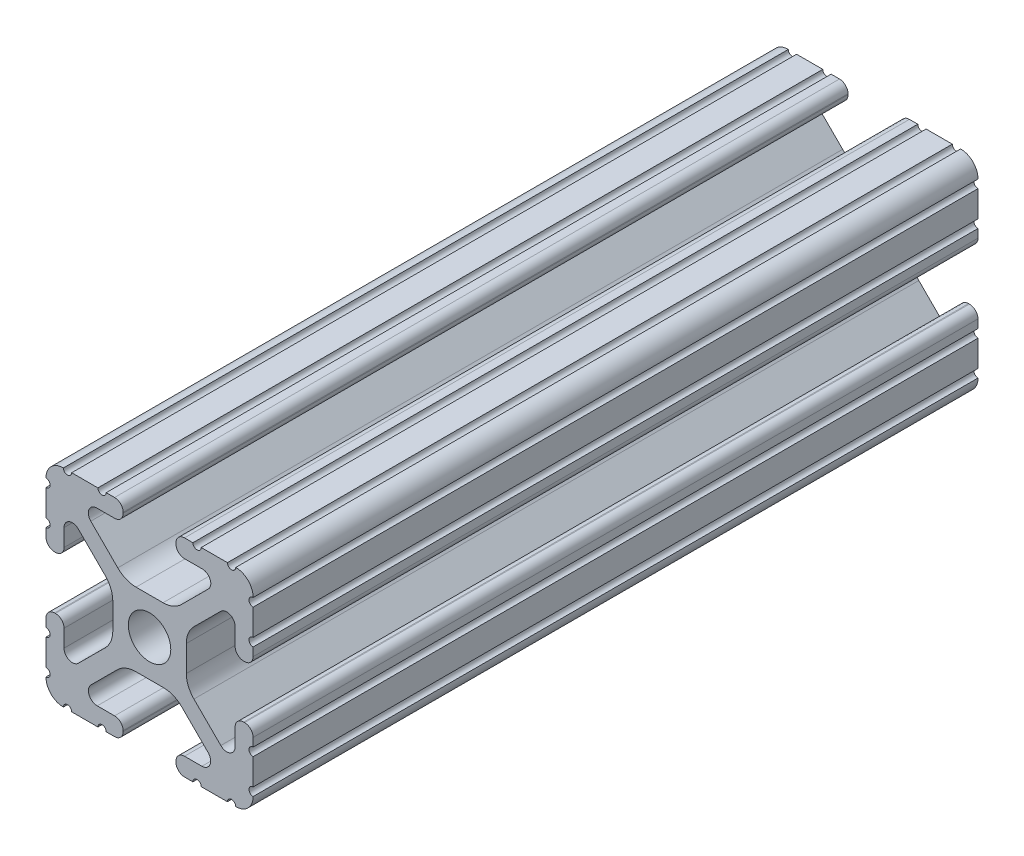
SolidWorks part; units mm, degrees
ref_plane "Front Plane" through (0, 0, 0) normal (0, 0, 1) x (1, 0, 0)
ref_plane "Top Plane" through (0, 0, 0) normal (0, 1, 0) x (1, 0, 0)
ref_plane "Right Plane" through (0, 0, 0) normal (1, 0, 0) x (0, 0, -1)
sketch "Sketch1" plane through (0, 0, 0) normal (0, 0, 1) x (1, 0, 0)
  line L88 (-7.1797, -8.6452) -> (-3.9523, -5.4237)
  line L89 (-1.7093, -4.4958) -> (1.7093, -4.4958)
  line L90 (3.9523, -5.4237) -> (7.1797, -8.6452)
  line L91 (6.4164, -10.4902) -> (4.2875, -10.4902)
  line L92 (3.2385, -11.5392) -> (3.2385, -11.651)
  line L93 (4.2875, -12.7) -> (5.3171, -12.7)
  line L94 (6.3331, -12.7) -> (9.5504, -12.7)
  line L95 (12.7, -9.5504) -> (12.7, -6.3331)
  line L96 (12.7, -5.3171) -> (12.7, -4.2875)
  line L97 (11.651, -3.2385) -> (11.5392, -3.2385)
  line L98 (10.4902, -4.2875) -> (10.4902, -6.4021)
  line L99 (8.7371, -7.1294) -> (5.441, -3.8408)
  line L100 (4.5085, -1.5932) -> (4.5085, 1.5932)
  line L101 (5.441, 3.8408) -> (8.7371, 7.1294)
  line L102 (10.4902, 6.4021) -> (10.4902, 4.2875)
  line L103 (11.5392, 3.2385) -> (11.651, 3.2385)
  line L104 (12.7, 4.2875) -> (12.7, 5.3171)
  line L105 (12.7, 6.3331) -> (12.7, 9.5504)
  line L106 (9.5504, 12.7) -> (6.3331, 12.7)
  line L107 (5.3171, 12.7) -> (4.2875, 12.7)
  line L108 (3.2385, 11.651) -> (3.2385, 11.5392)
  line L109 (4.2875, 10.4902) -> (6.4768, 10.4902)
  line L110 (7.207, 8.7244) -> (3.8983, 5.4232)
  line L111 (1.6558, 4.4958) -> (-1.6558, 4.4958)
  line L112 (-3.8983, 5.4232) -> (-7.207, 8.7244)
  line L113 (-6.4768, 10.4902) -> (-4.2875, 10.4902)
  line L114 (-3.2385, 11.5392) -> (-3.2385, 11.651)
  line L115 (-4.2875, 12.7) -> (-5.3171, 12.7)
  line L116 (-6.3331, 12.7) -> (-9.5504, 12.7)
  line L117 (-12.7, 9.5504) -> (-12.7, 6.3331)
  line L118 (-12.7, 5.3171) -> (-12.7, 4.2875)
  line L119 (-11.651, 3.2385) -> (-11.5392, 3.2385)
  line L120 (-10.4902, 4.2875) -> (-10.4902, 6.4021)
  line L121 (-8.7371, 7.1294) -> (-5.441, 3.8408)
  line L122 (-4.5085, 1.5932) -> (-4.5085, -1.5932)
  line L123 (-5.441, -3.8408) -> (-8.7371, -7.1294)
  line L124 (-10.4902, -6.4021) -> (-10.4902, -4.2875)
  line L125 (-11.5392, -3.2385) -> (-11.651, -3.2385)
  line L126 (-12.7, -4.2875) -> (-12.7, -5.3171)
  line L127 (-12.7, -6.3331) -> (-12.7, -9.5504)
  line L128 (-9.5504, -12.7) -> (-6.3331, -12.7)
  line L129 (-5.3171, -12.7) -> (-4.2875, -12.7)
  line L130 (-3.2385, -11.651) -> (-3.2385, -11.5392)
  line L131 (-4.2875, -10.4902) -> (-6.4164, -10.4902)
  circle A1 centre (0, 0) radius 2.6035
  arc A104 (-7.1797, -8.6452) -> (-6.4164, -10.4902) centre (-6.4164, -9.4098) ccw
  arc A105 (-1.7093, -4.4958) -> (-3.9523, -5.4237) centre (-1.7093, -7.6708) ccw
  arc A106 (3.9523, -5.4237) -> (1.7093, -4.4958) centre (1.7093, -7.6708) ccw
  arc A107 (6.4164, -10.4902) -> (7.1797, -8.6452) centre (6.4164, -9.4098) ccw
  arc A108 (4.2875, -10.4902) -> (3.2385, -11.5392) centre (4.2875, -11.5392) ccw
  arc A109 (3.2385, -11.651) -> (4.2875, -12.7) centre (4.2875, -11.651) ccw
  arc A110 (6.3331, -12.7) -> (5.3171, -12.7) centre (5.8251, -12.7) ccw
  arc A111 (10.5664, -12.6998) -> (9.5504, -12.7) centre (10.0584, -12.7) ccw
  arc A112 (10.5664, -12.6998) -> (12.6998, -10.5664) centre (10.5918, -10.5918) ccw
  arc A113 (12.7, -9.5504) -> (12.6998, -10.5664) centre (12.7, -10.0584) ccw
  arc A114 (12.7, -5.3171) -> (12.7, -6.3331) centre (12.7, -5.8251) ccw
  arc A115 (12.7, -4.2875) -> (11.651, -3.2385) centre (11.651, -4.2875) ccw
  arc A116 (11.5392, -3.2385) -> (10.4902, -4.2875) centre (11.5392, -4.2875) ccw
  arc A117 (8.7371, -7.1294) -> (10.4902, -6.4021) centre (9.4628, -6.4021) ccw
  arc A118 (4.5085, -1.5932) -> (5.441, -3.8408) centre (7.6835, -1.5932) ccw
  arc A119 (5.441, 3.8408) -> (4.5085, 1.5932) centre (7.6835, 1.5932) ccw
  arc A120 (10.4902, 6.4021) -> (8.7371, 7.1294) centre (9.4628, 6.4021) ccw
  arc A121 (10.4902, 4.2875) -> (11.5392, 3.2385) centre (11.5392, 4.2875) ccw
  arc A122 (11.651, 3.2385) -> (12.7, 4.2875) centre (11.651, 4.2875) ccw
  arc A123 (12.7, 6.3331) -> (12.7, 5.3171) centre (12.7, 5.8251) ccw
  arc A124 (12.6998, 10.5664) -> (12.7, 9.5504) centre (12.7, 10.0584) ccw
  arc A125 (12.6998, 10.5664) -> (10.5664, 12.6998) centre (10.5918, 10.5918) ccw
  arc A126 (9.5504, 12.7) -> (10.5664, 12.6998) centre (10.0584, 12.7) ccw
  arc A127 (5.3171, 12.7) -> (6.3331, 12.7) centre (5.8251, 12.7) ccw
  arc A128 (4.2875, 12.7) -> (3.2385, 11.651) centre (4.2875, 11.651) ccw
  arc A129 (3.2385, 11.5392) -> (4.2875, 10.4902) centre (4.2875, 11.5392) ccw
  arc A130 (7.207, 8.7244) -> (6.4768, 10.4902) centre (6.4768, 9.4563) ccw
  arc A131 (1.6558, 4.4958) -> (3.8983, 5.4232) centre (1.6558, 7.6708) ccw
  arc A132 (-3.8983, 5.4232) -> (-1.6558, 4.4958) centre (-1.6558, 7.6708) ccw
  arc A133 (-6.4768, 10.4902) -> (-7.207, 8.7244) centre (-6.4768, 9.4563) ccw
  arc A134 (-4.2875, 10.4902) -> (-3.2385, 11.5392) centre (-4.2875, 11.5392) ccw
  arc A135 (-3.2385, 11.651) -> (-4.2875, 12.7) centre (-4.2875, 11.651) ccw
  arc A136 (-6.3331, 12.7) -> (-5.3171, 12.7) centre (-5.8251, 12.7) ccw
  arc A137 (-10.5664, 12.6998) -> (-9.5504, 12.7) centre (-10.0584, 12.7) ccw
  arc A138 (-10.5664, 12.6998) -> (-12.6998, 10.5664) centre (-10.5918, 10.5918) ccw
  arc A139 (-12.7, 9.5504) -> (-12.6998, 10.5664) centre (-12.7, 10.0584) ccw
  arc A140 (-12.7, 5.3171) -> (-12.7, 6.3331) centre (-12.7, 5.8251) ccw
  arc A141 (-12.7, 4.2875) -> (-11.651, 3.2385) centre (-11.651, 4.2875) ccw
  arc A142 (-11.5392, 3.2385) -> (-10.4902, 4.2875) centre (-11.5392, 4.2875) ccw
  arc A143 (-8.7371, 7.1294) -> (-10.4902, 6.4021) centre (-9.4628, 6.4021) ccw
  arc A144 (-4.5085, 1.5932) -> (-5.441, 3.8408) centre (-7.6835, 1.5932) ccw
  arc A145 (-5.441, -3.8408) -> (-4.5085, -1.5932) centre (-7.6835, -1.5932) ccw
  arc A146 (-10.4902, -6.4021) -> (-8.7371, -7.1294) centre (-9.4628, -6.4021) ccw
  arc A147 (-10.4902, -4.2875) -> (-11.5392, -3.2385) centre (-11.5392, -4.2875) ccw
  arc A148 (-11.651, -3.2385) -> (-12.7, -4.2875) centre (-11.651, -4.2875) ccw
  arc A149 (-12.7, -6.3331) -> (-12.7, -5.3171) centre (-12.7, -5.8251) ccw
  arc A150 (-12.6998, -10.5664) -> (-12.7, -9.5504) centre (-12.7, -10.0584) ccw
  arc A151 (-12.6998, -10.5664) -> (-10.5664, -12.6998) centre (-10.5918, -10.5918) ccw
  arc A152 (-9.5504, -12.7) -> (-10.5664, -12.6998) centre (-10.0584, -12.7) ccw
  arc A153 (-5.3171, -12.7) -> (-6.3331, -12.7) centre (-5.8251, -12.7) ccw
  arc A154 (-4.2875, -12.7) -> (-3.2385, -11.651) centre (-4.2875, -11.651) ccw
  arc A155 (-3.2385, -11.5392) -> (-4.2875, -10.4902) centre (-4.2875, -11.5392) ccw
extrude "Boss-Extrude1" add sketch "Sketch1" along normal mid plane 88.9
equation "\"deep\"= 6in"
equation "\"high\"= 24in"
equation "\"wide\"= 14in"
equation "\"Length@Boss-Extrude1\"    = \"deep\""
equation "\"front wide\"= 16in"
